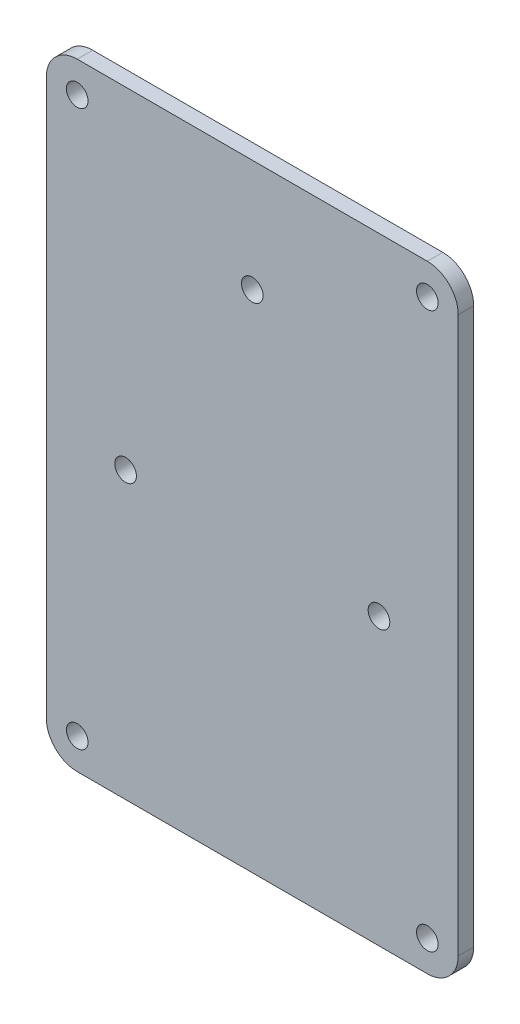
SolidWorks part; units mm, degrees
ref_plane "Ön Düzlem" through (0, 0, 0) normal (0, 0, 1) x (1, 0, 0)
ref_plane "Üst Düzlem" through (0, 0, 0) normal (0, 1, 0) x (1, 0, 0)
ref_plane "Sağ Düzlem" through (0, 0, 0) normal (1, 0, 0) x (0, 0, -1)
sketch "Çizim1" plane through (0, 0, 0) normal (0, 0, 1) x (1, 0, 0)
  line L0 (22.0396, -38.5046) -> (22.0396, 69.3474)
  line L1 (16.0396, 75.3474) -> (-51.9604, 75.3474)
  line L2 (-57.9604, 69.3474) -> (-57.9604, -38.5046)
  line L3 (-51.9604, -44.5046) -> (16.0396, -44.5046)
  arc A0 (16.0396, -44.5046) -> (22.0396, -38.5046) centre (16.0396, -38.5046) ccw
  arc A1 (22.0396, 69.3474) -> (16.0396, 75.3474) centre (16.0396, 69.3474) ccw
  arc A2 (-51.9604, 75.3474) -> (-57.9604, 69.3474) centre (-51.9604, 69.3474) ccw
  arc A3 (-57.9604, -38.5046) -> (-51.9604, -44.5046) centre (-51.9604, -38.5046) ccw
  circle A4 centre (-51.9604, -38.5046) radius 2.1
  circle A5 centre (16.0396, -38.5046) radius 2.1
  circle A6 centre (16.0396, 69.3474) radius 2.1
  circle A7 centre (-51.9604, 69.3474) radius 2.1
extrude "Yükseklik-Ekstrüzyon1" add sketch "Çizim1" along normal blind 3
sketch "Çizim2" plane through (0, 0, 0) normal (0, 0, -1) x (-1, 0, 0)
  circle A0 centre (17.9604, 53.5786) radius 2.1
  circle A1 centre (42.5681, 10.9568) radius 2.1
  circle A2 centre (-6.6473, 10.9568) radius 2.1
extrude "Kes-Ekstrüzyon1" cut sketch "Çizim2" against normal blind 10
